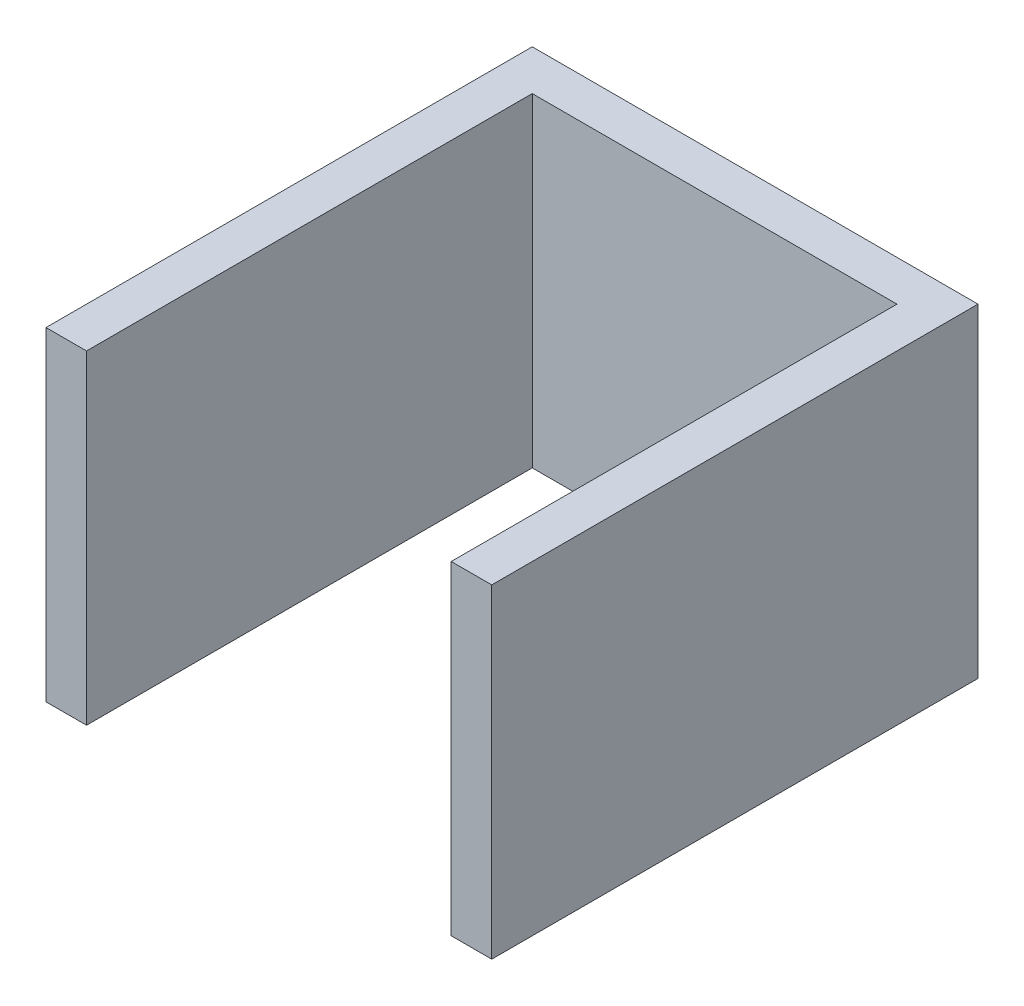
SolidWorks part; units mm, degrees
ref_plane "Front Plane" through (0, 0, 0) normal (0, 0, 1) x (1, 0, 0)
ref_plane "Top Plane" through (0, 0, 0) normal (0, 1, 0) x (1, 0, 0)
ref_plane "Right Plane" through (0, 0, 0) normal (1, 0, 0) x (0, 0, -1)
sketch "Sketch1" plane through (0, 0, 0) normal (0, 1, 0) x (1, 0, 0)
  line L0 (0, 0) -> (0, 120)
  line L1 (0, 120) -> (-110, 120)
  line L2 (-110, 120) -> (-110, 0)
  line L3 (-110, 0) -> (-100, 0)
  line L4 (-100, 0) -> (-100, 110)
  line L5 (-100, 110) -> (-10, 110)
  line L6 (-10, 110) -> (-10, 0)
  line L7 (-10, 0) -> (0, 0)
  dimension "D1" = 110
  dimension "D2" = 120
  dimension "D3" = 10
  dimension "D4" = 10
  dimension "D5" = 10
extrude "Boss-Extrude1" add sketch "Sketch1" along normal blind 80
